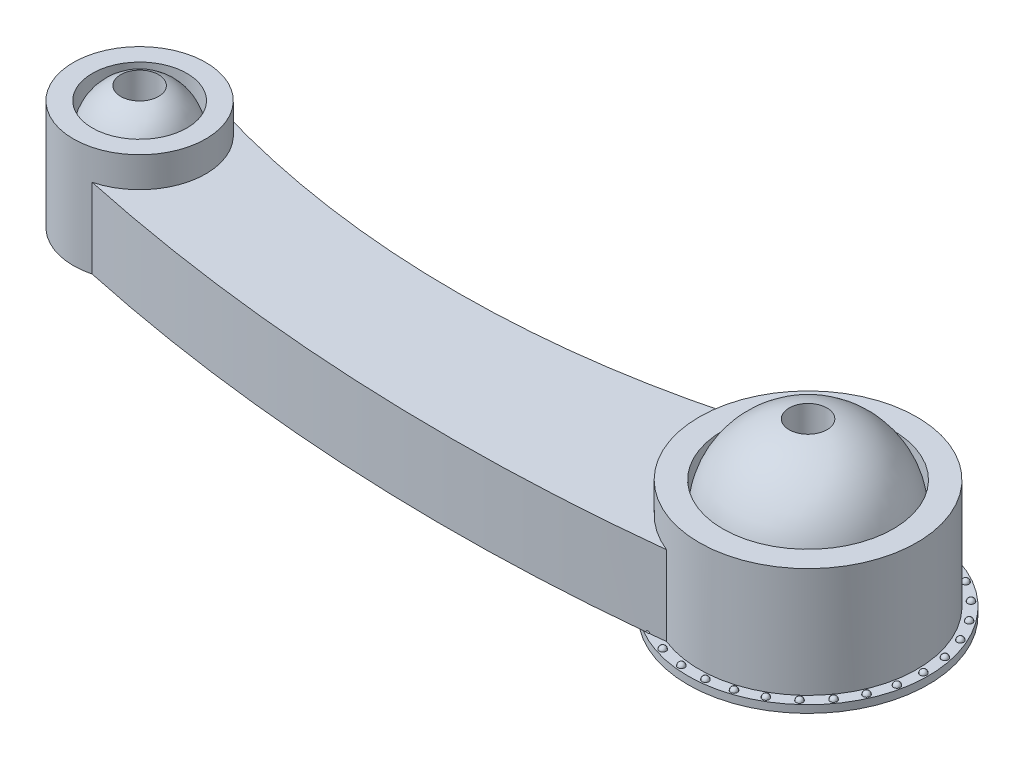
SolidWorks part; units mm, degrees
ref_plane "Front Plane" through (0, 0, 0) normal (0, 0, 1) x (1, 0, 0)
ref_plane "Top Plane" through (0, 0, 0) normal (0, 1, 0) x (1, 0, 0)
ref_plane "Right Plane" through (0, 0, 0) normal (1, 0, 0) x (0, 0, -1)
sketch "Sketch2" plane through (0, 0, 0) normal (0, 1, 0) x (1, 0, 0)
  arc A0 (-10.6837, -26.6912) -> (-24.293, 15.3757) centre (0, 0) ccw
  arc A1 (-169.318, 14.9945) -> (-170.5841, -18.4953) centre (-174.993, -1.5598) ccw
  arc A2 (-169.318, 14.9945) -> (-24.293, 15.3757) centre (-97.4385, 256.004) ccw
  arc A3 (-170.5841, -18.4953) -> (-10.6837, -26.6912) centre (-65.2139, 473.3443) ccw
extrude "Boss-Extrude1" add sketch "Sketch2" along normal blind 21
sketch "Sketch3" plane through (0, 21, 0) normal (0, 1, 0) x (1, 0, 0)
  circle A0 centre (0, 0) radius 28.75
  circle A1 centre (0, 0) radius 22.5
  circle A2 centre (-174.993, -1.5598) radius 17.5
  circle A3 centre (-174.993, -1.5598) radius 12.5
  dimension "D1" = 25
  dimension "D2" = 45
extrude "Boss-Extrude2" add sketch "Sketch3" along normal blind 8
sketch "Sketch4" plane through (0, 0, 0) normal (0, 0, 1) x (1, 0, 0)
  line L4 (-28.75, 29) -> (-28.75, 0) construction
  line L5 (-170.5841, 0) -> (-10.6837, 0) construction
sketch "Sketch9" plane through (0, 21, 0) normal (0, 1, 0) x (1, 0, 0)
  line L0 (-22.5, 0) -> (22.5, 0) construction
  circle A0 centre (0, 0) radius 22.5 construction
  circle A1 centre (0, 0) radius 22.5 construction
sketch "Sketch11" plane through (0, 21, 0) normal (0, 1, 0) x (1, 0, 0)
  line L0 (-22.5, 0) -> (22.5, 0) construction
  line L1 (-22.5, 0) -> (22.5, 0)
  arc A0 (22.5, 0) -> (-22.5, 0) centre (0, 0) ccw
revolve "Revolve8" add sketch "Sketch11" angle 180 about L1
sketch "Sketch12" plane through (0, 21, 0) normal (0, 1, 0) x (1, 0, 0)
  line L0 (-187.493, -1.5598) -> (-162.493, -1.5598)
  circle A0 centre (-174.993, -1.5598) radius 12.5 construction
  circle A1 centre (-174.993, -1.5598) radius 12.5 construction
  arc A2 (-162.493, -1.5598) -> (-187.493, -1.5598) centre (-174.993, -1.5598) ccw
revolve "Revolve9" add sketch "Sketch12" angle 180 about L0
sketch "Sketch13" plane through (0, 0, 0) normal (0, -1, 0) x (1, 0, 0)
  circle A0 centre (-174.993, 1.5598) radius 7.5
  circle A1 centre (0, 0) radius 7.5
  dimension "D1" = 15
  dimension "D2" = 15
extrude "Boss-Extrude3" add sketch "Sketch13" along normal blind 10
ref_plane "Plane1" through (0, 32, 0) normal (0, -1, 0) x (-1, 0, 0)
sketch "Sketch14" plane through (0, 32, 0) normal (0, -1, 0) x (-1, 0, 0)
  circle A0 centre (0, 0) radius 5
  circle A1 centre (174.993, -1.5598) radius 5
  dimension "D1" = 10
  dimension "D2" = 10
extrude "Cut-Extrude1" cut sketch "Sketch14" against normal through all contours A0
sketch "Sketch15" plane through (0, 32, 0) normal (0, -1, 0) x (-1, 0, 0)
  circle A0 centre (174.993, -1.5598) radius 5
  dimension "D1" = 10
extrude "Cut-Extrude2" cut sketch "Sketch15" against normal mid plane 14.86
sketch "Sketch16" plane through (0, 32, 0) normal (0, 1, 0) x (1, 0, 0)
  circle A0 centre (0, 0) radius 2.5
  dimension "D1" = 5
extrude "Cut-Extrude3" cut sketch "Sketch16" against normal through all
sketch "Sketch17" plane through (0, 24.57, 0) normal (0, 1, 0) x (1, 0, 0)
  circle A0 centre (-174.993, -1.5598) radius 2.5
  dimension "D1" = 5
extrude "Cut-Extrude4" cut sketch "Sketch17" against normal through all
sketch "Sketch18" plane through (0, 0, 0) normal (0, -1, 0) x (1, 0, 0)
  circle A0 centre (0, 0) radius 31.75
  circle A1 centre (0, 0) radius 2.5 construction
  circle A2 centre (0, 0) radius 2.5
  dimension "D1" = 63.5
extrude "Boss-Extrude4" add sketch "Sketch18" along normal blind 2
sketch "Sketch19" plane through (0, 0, 0) normal (0, 1, 0) x (1, 0, 0)
  line L0 (29.5661, 0) -> (31.3661, 0)
  arc A0 (31.3661, 0) -> (29.5661, 0) centre (30.4661, 0) ccw
  dimension "D1" = 1.8
revolve "Revolve10" add sketch "Sketch19" angle 360 about L0
pattern_circular "CirPattern1" count 30 over 360 about axis through (0, 0, 0) along (0, 1, 0) of "Revolve10"
